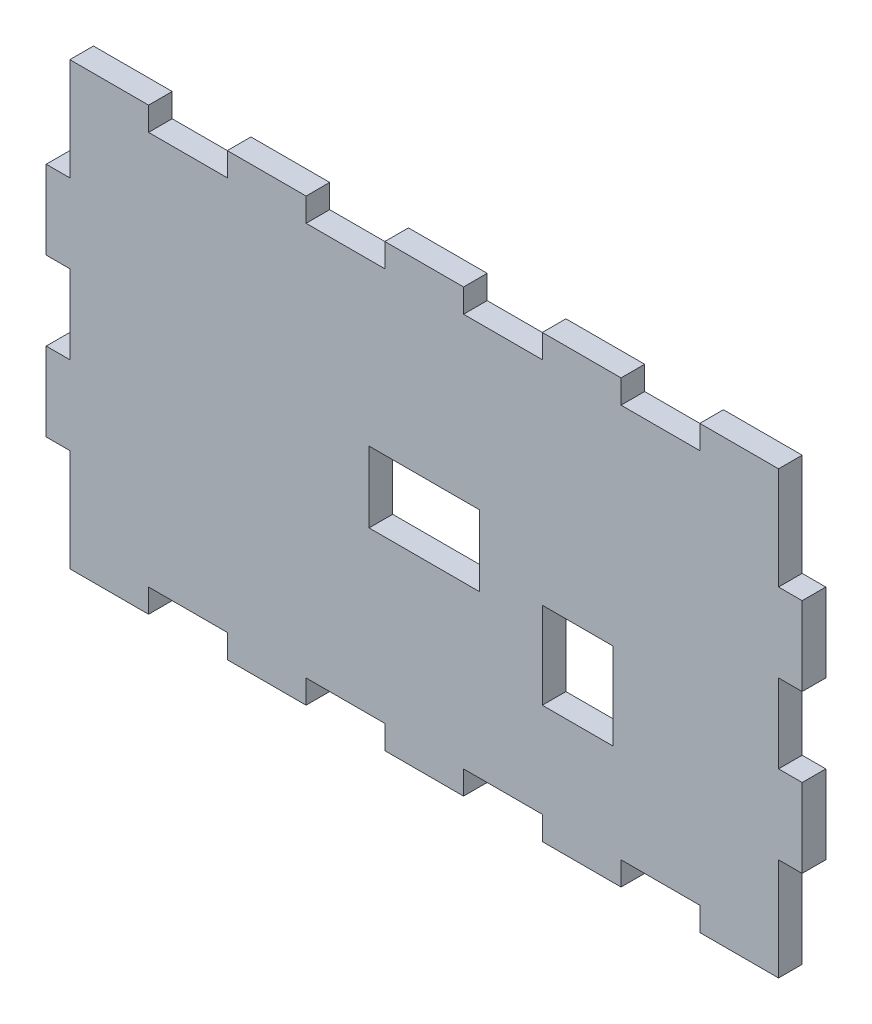
SolidWorks part; units mm, degrees
ref_plane "Front Plane" through (0, 0, 0) normal (0, 0, 1) x (1, 0, 0)
ref_plane "Top Plane" through (0, 0, 0) normal (0, 1, 0) x (1, 0, 0)
ref_plane "Right Plane" through (0, 0, 0) normal (1, 0, 0) x (0, 0, -1)
sketch "Sketch1" plane through (0, 0, 0) normal (0, 0, 1) x (1, 0, 0)
  line L0 (25, 28) -> (25, 25)
  line L1 (-46.5, 26.5) -> (46.5, 26.5) construction
  line L2 (-46.5, 26.5) -> (-46.5, -26.5) construction
  line L3 (-46.5, -26.5) -> (46.5, -26.5) construction
  line L4 (46.5, 26.5) -> (46.5, -26.5) construction
  line L5 (-46.5, 26.5) -> (46.5, -26.5) construction
  line L6 (-46.5, -26.5) -> (46.5, 26.5) construction
  line L7 (-5, 28) -> (5, 28)
  line L8 (-5, 28) -> (-5, 25)
  line L9 (-5, 25) -> (5, 25) construction
  line L10 (5, 28) -> (5, 25)
  line L11 (-5, 28) -> (5, 25) construction
  line L12 (-5, 25) -> (5, 28) construction
  line L13 (15, 28) -> (25, 28)
  line L14 (15, 28) -> (15, 25)
  line L15 (45, 28) -> (45, 25)
  line L16 (35, 28) -> (45, 28)
  line L17 (35, 28) -> (35, 25)
  line L18 (-15, 28) -> (-15, 25)
  line L19 (-25, 28) -> (-15, 28)
  line L20 (-25, 28) -> (-25, 25)
  line L21 (-35, 28) -> (-35, 25)
  line L22 (-45, 28) -> (-35, 28)
  line L23 (0, 0) -> (8.5024, 0) construction
  line L24 (-45, 28) -> (-45, 25)
  line L25 (-35, 25) -> (-25, 25)
  line L26 (-15, 25) -> (-5, 25)
  line L27 (5, 25) -> (15, 25)
  line L28 (0, 0) -> (0, 11.5614) construction
  line L29 (25, 25) -> (35, 25)
  line L30 (-48, 5) -> (-48, 15)
  line L31 (-48, -15) -> (-45, -15)
  line L32 (-45, -15) -> (-45, -25)
  line L33 (-48, -15) -> (-48, -5)
  line L34 (45, -28) -> (45, -25)
  line L35 (35, -28) -> (45, -28)
  line L36 (35, -28) -> (35, -25)
  line L37 (25, -25) -> (35, -25)
  line L38 (25, -28) -> (25, -25)
  line L39 (15, -28) -> (15, -25)
  line L40 (15, -28) -> (25, -28)
  line L41 (5, -25) -> (15, -25)
  line L42 (5, -28) -> (5, -25)
  line L43 (-5, -28) -> (5, -28)
  line L44 (-5, -28) -> (-5, -25)
  line L45 (-15, -25) -> (-5, -25)
  line L46 (-15, -28) -> (-15, -25)
  line L47 (-25, -28) -> (-15, -28)
  line L48 (-48, 5) -> (-45, 5)
  line L49 (-48, 5) -> (-48, -5) construction
  line L50 (-48, -5) -> (-45, -5)
  line L51 (-45, 5) -> (-45, -5)
  line L52 (-48, 5) -> (-45, -5) construction
  line L53 (-48, -5) -> (-45, 5) construction
  line L54 (-45, 25) -> (-45, 15)
  line L55 (-48, 15) -> (-45, 15)
  line L56 (-48, 25) -> (-45, 25) [skipped]
  line L57 (-25, -28) -> (-25, -25)
  line L58 (-35, -28) -> (-35, -25)
  line L59 (-35, -25) -> (-25, -25)
  line L60 (-45, -28) -> (-35, -28)
  line L61 (45, -15) -> (45, -25)
  line L62 (48, -15) -> (45, -15)
  line L63 (48, -15) -> (48, -5)
  line L64 (48, -5) -> (45, -5)
  line L65 (45, 5) -> (45, -5)
  line L66 (48, 5) -> (45, 5)
  line L67 (-48, -25) -> (-45, -25) [skipped]
  line L68 (48, 5) -> (48, 15)
  line L69 (48, 15) -> (45, 15)
  line L70 (45, 25) -> (45, 15)
  line L71 (-45, -28) -> (-45, -25)
  point P0 (0, 0)
  point P6 (0, 26.5)
  point P50 (-46.5, 0)
  dimension "D1" = 93
  dimension "D2" = 53
  dimension "D3" = 10
  dimension "D4" = 3
  dimension "D8" = 3
  dimension "D9" = 10
  dimension "D10" = 3
  dimension "D7" = 3
  dimension "D11" = 2
  dimension "D5" = 2
extrude "Boss-Extrude1" add sketch "Sketch1" along normal blind 3
sketch "Sketch2" plane through (0, 0, 3) normal (0, 0, 1) x (1, 0, 0)
  line L0 (-45, -15) -> (-45, -28) construction
  line L1 (15, -2) -> (24, -2)
  line L2 (15, -2) -> (15, -13)
  line L3 (15, -13) -> (24, -13)
  line L4 (24, -2) -> (24, -13)
  line L5 (15, -2) -> (24, -13) construction
  line L6 (15, -13) -> (24, -2) construction
  line L7 (5, -25) -> (15, -25) construction
  point P0 (19.5, -7.5)
  dimension "D1" = 9
  dimension "D2" = 11
  dimension "D3" = 60
  dimension "D4" = 12
extrude "Cut-Extrude1" cut sketch "Sketch2" against normal blind 3
sketch "Sketch3" plane through (0, 0, 3) normal (0, 0, 1) x (1, 0, 0)
  line L2 (-7, -4.5) -> (7, -4.5)
  line L3 (-7, -4.5) -> (-7, 4.5)
  line L4 (-7, 4.5) -> (7, 4.5)
  line L5 (7, -4.5) -> (7, 4.5)
  line L6 (-7, -4.5) -> (7, 4.5) construction
  line L7 (-7, 4.5) -> (7, -4.5) construction
  point P0 (0, 0)
  point P1 (0, 0)
  dimension "D2" = 14
  dimension "D3" = 9
extrude "Cut-Extrude2" cut sketch "Sketch3" against normal blind 3
